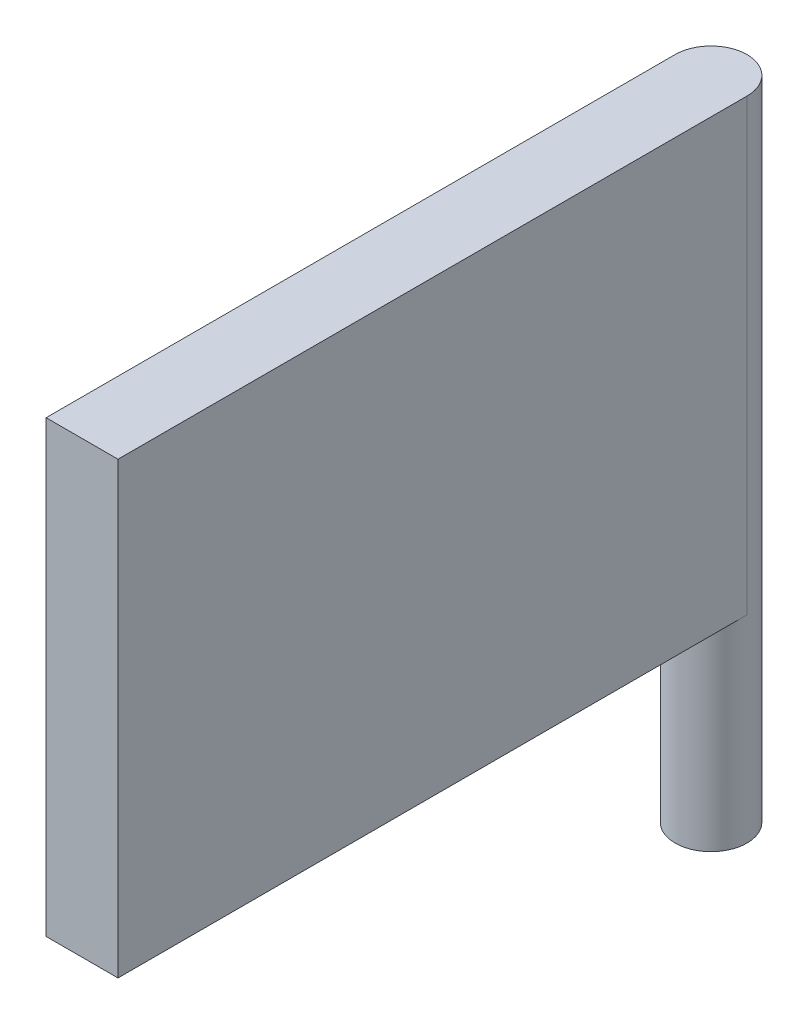
SolidWorks part; units mm, degrees
ref_plane "Front Plane" through (0, 0, 0) normal (0, 0, 1) x (1, 0, 0)
ref_plane "Top Plane" through (0, 0, 0) normal (0, 1, 0) x (1, 0, 0)
ref_plane "Right Plane" through (0, 0, 0) normal (1, 0, 0) x (0, 0, -1)
sketch "Sketch1" plane through (0, 0, 0) normal (0, 1, 0) x (1, 0, 0)
  circle A0 centre (0, 0) radius 4
extrude "Boss-Extrude1" add sketch "Sketch1" along normal blind 72
sketch "Sketch2" plane through (0, 0, 0) normal (0, 0, 1) x (1, 0, 0)
  line L0 (4, 0) -> (4, 72) construction
  line L1 (-4, 72) -> (4, 72)
  line L2 (-4, 72) -> (-4, 22)
  line L3 (-4, 22) -> (4, 22)
  line L4 (4, 72) -> (4, 22)
  dimension "D1" = 50
extrude "Boss-Extrude2" add sketch "Sketch2" along normal blind 70
